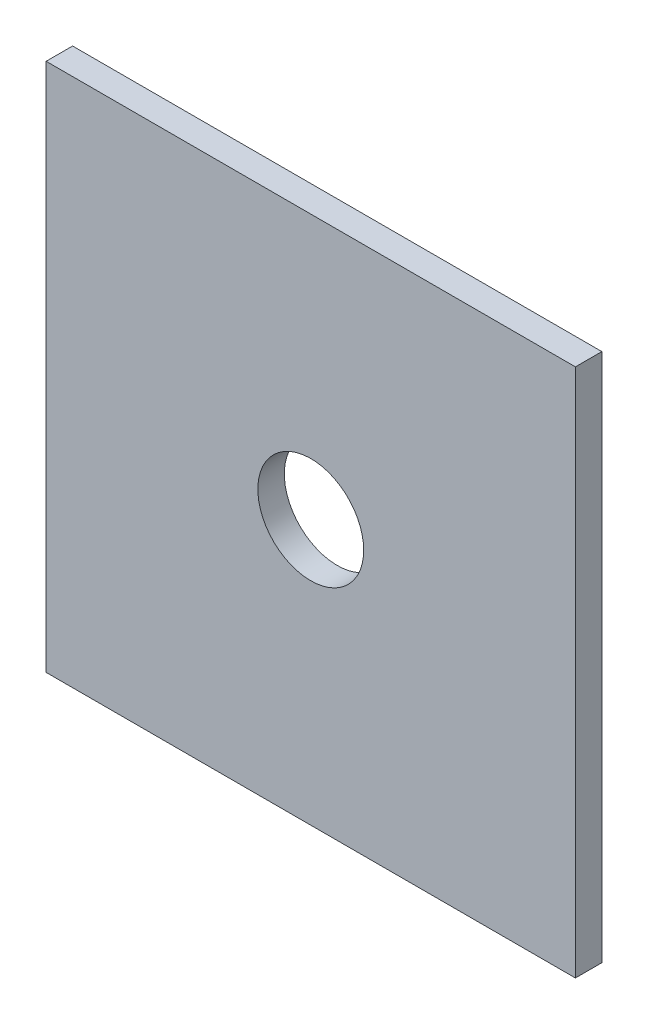
SolidWorks part; units mm, degrees
ref_plane "Front Plane" through (0, 0, 0) normal (0, 0, 1) x (1, 0, 0)
ref_plane "Top Plane" through (0, 0, 0) normal (0, 1, 0) x (1, 0, 0)
ref_plane "Right Plane" through (0, 0, 0) normal (1, 0, 0) x (0, 0, -1)
sketch "Sketch1" plane through (0, 0, 0) normal (0, 0, 1) x (1, 0, 0)
  line L1 (-20, -20) -> (20, -20)
  line L2 (-20, -20) -> (-20, 20)
  line L3 (-20, 20) -> (20, 20)
  line L4 (20, -20) -> (20, 20)
  line L5 (-20, -20) -> (20, 20) construction
  line L6 (-20, 20) -> (20, -20) construction
  point P0 (0, 0)
  dimension "D1" = 40
  dimension "D2" = 40
extrude "Boss-Extrude1" add sketch "Sketch1" along normal mid plane 2
sketch "Sketch2" plane through (0, 0, 1) normal (0, 0, 1) x (1, 0, 0)
  circle A0 centre (0, 0) radius 4
  dimension "D1" = 8
extrude "Cut-Extrude1" cut sketch "Sketch2" against normal through all
